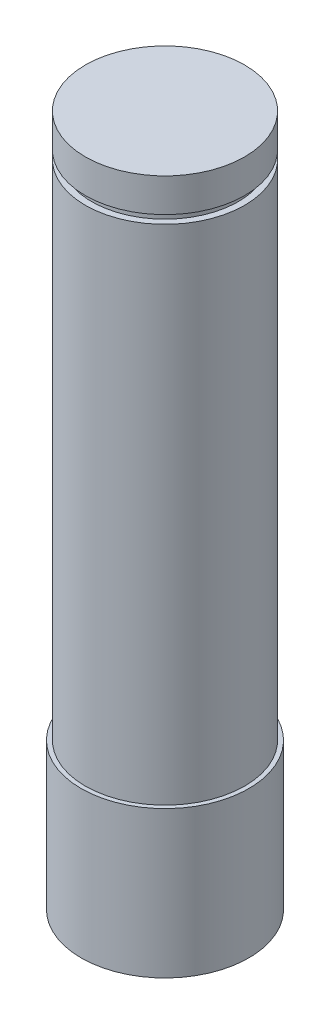
SolidWorks part; units mm, degrees
ref_plane "Front" through (0, 0, 0) normal (0, 0, 1) x (1, 0, 0)
ref_plane "Top" through (0, 0, 0) normal (0, 1, 0) x (1, 0, 0)
ref_plane "Right" through (0, 0, 0) normal (1, 0, 0) x (0, 0, -1)
sketch "Sketch1" plane through (0, 0, 0) normal (0, 0, 1) x (1, 0, 0)
  line L0 (0, 0) -> (0, 16.5) construction
  line L1 (0, 16.5) -> (-1.9, 16.5)
  line L2 (-1.9, 16.5) -> (-1.9, 15.7)
  line L3 (-1.9, 3.5) -> (-2, 3.5)
  line L4 (-2, 3.5) -> (-2, 0)
  line L5 (-2, 0) -> (0, 0)
  line L6 (0, 0) -> (0, 16.5)
  line L7 (-1.9, 15.5) -> (-1.9, 3.5)
  line L8 (-1.9, 15.7) -> (-1.75, 15.7)
  line L10 (-1.9, 15.5) -> (-1.75, 15.5)
  line L11 (-1.75, 15.7) -> (-1.75, 15.5)
  dimension "D1" = 3.5
  dimension "D2" = 13
  dimension "D3" = 3.8
  dimension "D4" = 4
  dimension "D5" = 0.15
  dimension "D6" = 0.2
  dimension "D7" = 1
revolve "Revolve1" add sketch "Sketch1" angle 360 about L0
